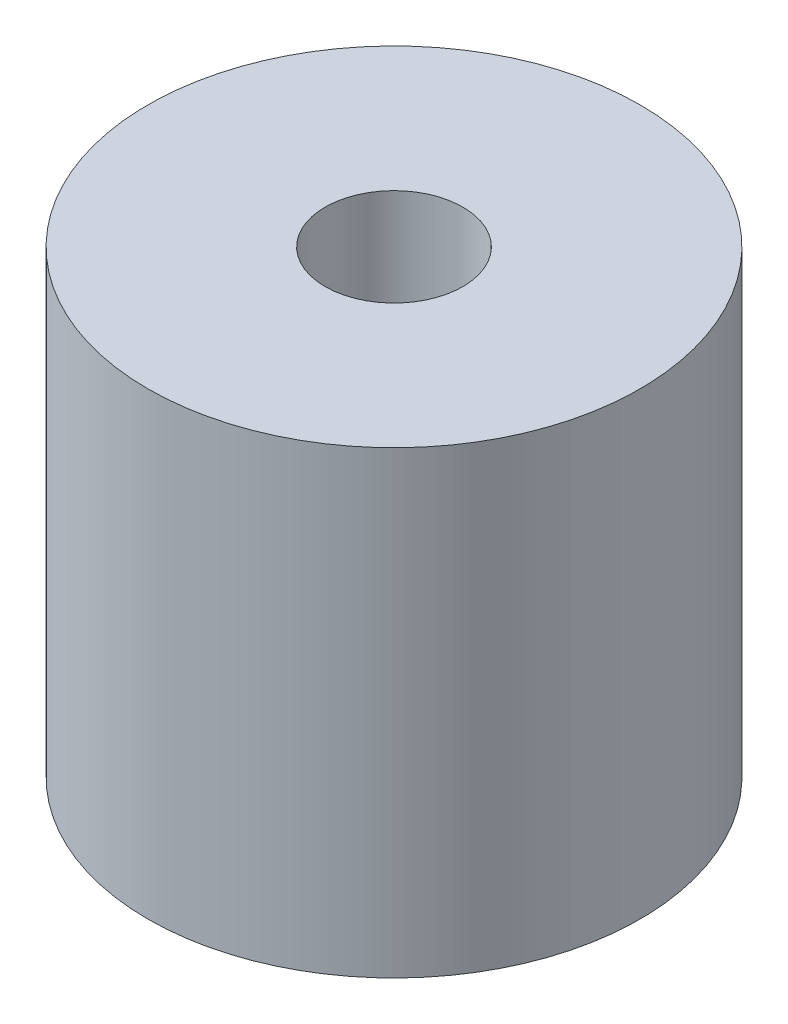
SolidWorks part; units mm, degrees
ref_plane "Front Plane" through (0, 0, 0) normal (0, 0, 1) x (1, 0, 0)
ref_plane "Top Plane" through (0, 0, 0) normal (0, 1, 0) x (1, 0, 0)
ref_plane "Right Plane" through (0, 0, 0) normal (1, 0, 0) x (0, 0, -1)
sketch "Sketch1" plane through (0, 0, 0) normal (0, 1, 0) x (1, 0, 0)
  circle A1 centre (0, 0) radius 2.1
  circle A2 centre (0, 0) radius 7.5
  dimension "D1" = 4.2
  dimension "D2" = 15
extrude "Boss-Extrude1" add sketch "Sketch1" along normal blind 14
